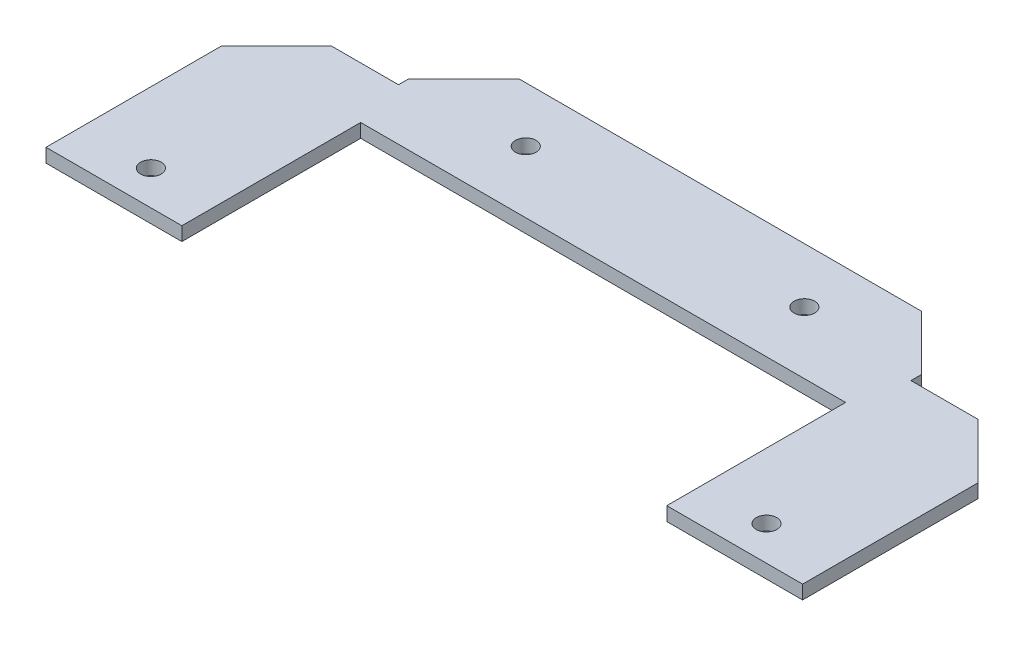
SolidWorks part; units mm, degrees
ref_plane "Front Plane" through (0, 0, 0) normal (0, 0, 1) x (1, 0, 0)
ref_plane "Top Plane" through (0, 0, 0) normal (0, 1, 0) x (1, 0, 0)
ref_plane "Right Plane" through (0, 0, 0) normal (1, 0, 0) x (0, 0, -1)
sketch "Sketch1" plane through (0, 0, 0) normal (0, 1, 0) x (1, 0, 0)
  line L0 (0, 0) -> (19.75, 0)
  line L1 (19.75, 0) -> (19.75, 26)
  line L2 (19.75, 26) -> (90.25, 26)
  line L4 (84.25, 43) -> (25.75, 43)
  line L5 (17.75, 35) -> (17.75, 33.5)
  line L6 (17.75, 33.5) -> (8, 33.5)
  line L7 (0, 25.5) -> (0, 0)
  line L8 (0, 25.5) -> (8, 33.5)
  line L9 (17.75, 35) -> (25.75, 43)
  line L10 (55, 51.8004) -> (55, -8.0119) construction
  line L11 (92.25, 35) -> (84.25, 43)
  line L12 (110, 25.5) -> (102, 33.5)
  line L13 (110, 25.5) -> (110, 0)
  line L14 (92.25, 33.5) -> (102, 33.5)
  line L15 (92.25, 35) -> (92.25, 33.5)
  line L16 (90.25, 0) -> (90.25, 26)
  line L17 (110, 0) -> (90.25, 0)
  circle A0 centre (10.25, 5) radius 1.5
  circle A1 centre (34.75, 35) radius 1.5
  circle A2 centre (75.25, 35) radius 1.5
  circle A3 centre (99.75, 5) radius 1.5
  point P18 (55, 43)
  point P19 (55, 26)
  dimension "D2" = 3
  dimension "D6" = 3
  dimension "D13" = 225
  dimension "D14" = 8
  dimension "D1" = 28.5
  dimension "D3" = 5
  dimension "D4" = 10.25
  dimension "D5" = 9.5
  dimension "D7" = 8
  dimension "D8" = 9
  dimension "D9" = 9.5
  dimension "D10" = 37.25
  dimension "D11" = 17.75
  dimension "D12" = 20.25
  dimension "D15" = 8
  dimension "D16" = 25.75
  dimension "D17" = 9.75
  dimension "D18" = 84.25
  dimension "D19" = 34.75
  dimension "D20" = 38
  dimension "D21" = 99.75
extrude "Boss-Extrude1" add sketch "Sketch1" along normal blind 2
